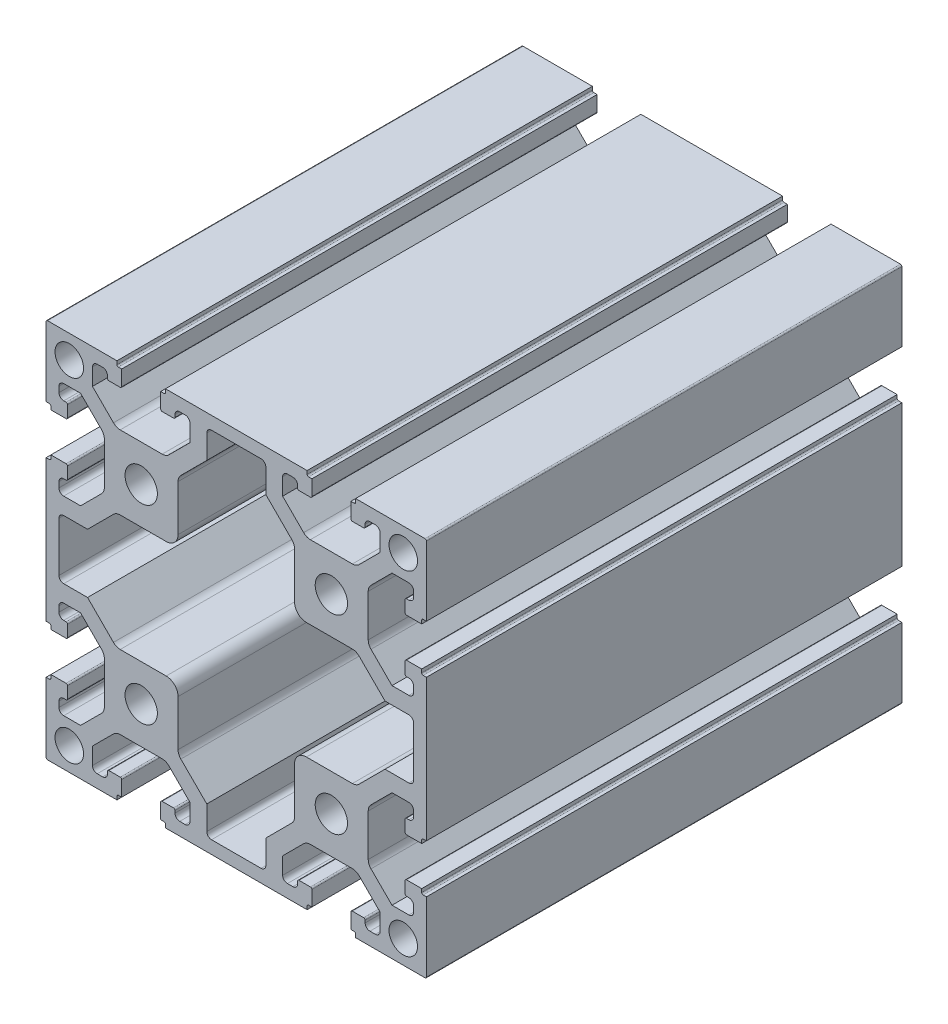
SolidWorks part; units mm, degrees
ref_plane "前视基准面" through (0, 0, 0) normal (0, 0, 1) x (1, 0, 0)
ref_plane "上视基准面" through (0, 0, 0) normal (0, 1, 0) x (1, 0, 0)
ref_plane "右视基准面" through (0, 0, 0) normal (1, 0, 0) x (0, 0, -1)
sketch "草图1" plane through (0, 0, 0) normal (0, 0, 1) x (1, 0, 0)
  line L0 (-25.5828, 38.6374) -> (-40.1828, 38.6374)
  line L1 (-40.4828, 38.3374) -> (-40.4828, 23.7374)
  line L2 (-33.236, 28.8874) -> (-36.7828, 28.8874)
  line L3 (-37.7828, 27.8874) -> (-37.7828, 26.7374)
  line L4 (-36.7828, 25.7374) -> (-36.2828, 25.7374)
  line L5 (-35.9828, 25.4374) -> (-35.9828, 23.0374)
  line L6 (-36.2828, 22.7374) -> (-39.4828, 22.7374)
  line L8 (-40.4828, 23.7374) -> (-39.7828, 23.7374)
  line L9 (-39.4828, 23.4374) -> (-39.4828, 22.7374)
  line L10 (-33.236, 28.8874) -> (-28.8186, 24.47)
  line L11 (-28.2328, 23.0558) -> (-28.2328, 14.219)
  line L12 (-28.8186, 12.8047) -> (-33.236, 8.3874)
  line L14 (-31.7697, 4.8474) -> (-26.3154, 10.3016)
  line L15 (-24.9012, 10.8874) -> (-15.2328, 10.8874)
  line L16 (-12.7328, 13.3874) -> (-12.7328, 23.0558)
  line L17 (-12.147, 24.47) -> (-6.6928, 29.9242)
  line L18 (-10.2328, 31.3905) -> (-14.6502, 26.9732)
  line L19 (-16.0644, 26.3874) -> (-24.9012, 26.3874)
  line L20 (-26.3154, 26.9732) -> (-30.7328, 31.3905)
  line L21 (-25.5828, 38.6374) -> (-25.5828, 37.9374)
  line L22 (-25.2828, 37.6374) -> (-24.5828, 37.6374)
  line L23 (-30.7328, 31.3905) -> (-30.7328, 34.9374)
  line L24 (-29.7328, 35.9374) -> (-28.5828, 35.9374)
  line L25 (-27.5828, 34.9374) -> (-27.5828, 34.4374)
  line L26 (-27.2828, 34.1374) -> (-24.8828, 34.1374)
  line L27 (-24.5828, 34.4374) -> (-24.5828, 37.6374)
  line L28 (-15.3828, 38.6374) -> (-4.9828, 38.6374)
  line L30 (-10.2328, 31.3905) -> (-10.2328, 34.9374)
  line L31 (-11.2328, 35.9374) -> (-12.3828, 35.9374)
  line L32 (-13.3828, 34.9374) -> (-13.3828, 34.4374)
  line L33 (-13.6828, 34.1374) -> (-16.0828, 34.1374)
  line L34 (-16.3828, 34.4374) -> (-16.3828, 37.6374)
  line L35 (-15.3828, 38.6374) -> (-15.3828, 37.9374)
  line L36 (-15.6828, 37.6374) -> (-16.3828, 37.6374)
  line L37 (-33.236, 8.3874) -> (-36.7828, 8.3874)
  line L38 (-37.7828, 9.3874) -> (-37.7828, 10.5374)
  line L39 (-36.7828, 11.5374) -> (-36.2828, 11.5374)
  line L40 (-35.9828, 11.8374) -> (-35.9828, 14.2374)
  line L41 (-36.2828, 14.5374) -> (-39.4828, 14.5374)
  line L42 (-40.4828, 13.5374) -> (-39.7828, 13.5374)
  line L43 (-39.4828, 13.8374) -> (-39.4828, 14.5374)
  line L44 (14.4172, 38.6374) -> (4.0172, 38.6374)
  line L47 (32.2703, 8.3874) -> (27.853, 12.8047)
  line L48 (27.2672, 14.219) -> (27.2672, 23.0558)
  line L49 (27.853, 24.47) -> (32.2703, 28.8874)
  line L50 (29.7672, 31.3905) -> (25.3498, 26.9732)
  line L51 (23.9356, 26.3874) -> (15.0988, 26.3874)
  line L52 (13.6846, 26.9732) -> (9.2672, 31.3905)
  line L53 (14.4172, 38.6374) -> (14.4172, 37.9374)
  line L54 (14.7172, 37.6374) -> (15.4172, 37.6374)
  line L55 (9.2672, 31.3905) -> (9.2672, 34.9374)
  line L56 (10.2672, 35.9374) -> (11.4172, 35.9374)
  line L57 (12.4172, 34.9374) -> (12.4172, 34.4374)
  line L58 (12.7172, 34.1374) -> (15.1172, 34.1374)
  line L59 (15.4172, 34.4374) -> (15.4172, 37.6374)
  line L60 (24.6172, 38.6374) -> (39.2172, 38.6374)
  line L61 (39.5172, 38.3374) -> (39.5172, 23.7374)
  line L62 (32.2703, 28.8874) -> (35.8172, 28.8874)
  line L63 (36.8172, 27.8874) -> (36.8172, 26.7374)
  line L64 (35.8172, 25.7374) -> (35.3172, 25.7374)
  line L65 (35.0172, 25.4374) -> (35.0172, 23.0374)
  line L66 (35.3172, 22.7374) -> (38.5172, 22.7374)
  line L68 (39.5172, 23.7374) -> (38.8172, 23.7374)
  line L69 (38.5172, 23.4374) -> (38.5172, 22.7374)
  line L70 (29.7672, 31.3905) -> (29.7672, 34.9374)
  line L71 (28.7672, 35.9374) -> (27.6172, 35.9374)
  line L72 (26.6172, 34.9374) -> (26.6172, 34.4374)
  line L73 (26.3172, 34.1374) -> (23.9172, 34.1374)
  line L74 (23.6172, 34.4374) -> (23.6172, 37.6374)
  line L75 (24.6172, 38.6374) -> (24.6172, 37.9374)
  line L76 (24.3172, 37.6374) -> (23.6172, 37.6374)
  line L77 (32.2703, 8.3874) -> (35.8172, 8.3874)
  line L78 (36.8172, 9.3874) -> (36.8172, 10.5374)
  line L79 (35.8172, 11.5374) -> (35.3172, 11.5374)
  line L80 (35.0172, 11.8374) -> (35.0172, 14.2374)
  line L81 (35.3172, 14.5374) -> (38.5172, 14.5374)
  line L82 (39.5172, 13.5374) -> (38.8172, 13.5374)
  line L83 (38.5172, 13.8374) -> (38.5172, 14.5374)
  line L84 (-4.9828, 38.6374) -> (4.0172, 38.6374)
  line L86 (-6.6928, 29.9242) -> (-6.6928, 34.9374)
  line L87 (-5.6928, 35.9374) -> (4.7272, 35.9374)
  line L88 (5.7272, 29.9242) -> (5.7272, 34.9374)
  line L89 (-25.5828, -41.3626) -> (-40.1828, -41.3626)
  line L90 (-40.4828, -41.0626) -> (-40.4828, -26.4626)
  line L91 (-33.236, -31.6126) -> (-36.7828, -31.6126)
  line L92 (-37.7828, -30.6126) -> (-37.7828, -29.4626)
  line L93 (-36.7828, -28.4626) -> (-36.2828, -28.4626)
  line L94 (-35.9828, -28.1626) -> (-35.9828, -25.7626)
  line L95 (-36.2828, -25.4626) -> (-39.4828, -25.4626)
  line L97 (-40.4828, -26.4626) -> (-39.7828, -26.4626)
  line L98 (-39.4828, -26.1626) -> (-39.4828, -25.4626)
  line L99 (-33.236, -31.6126) -> (-28.8186, -27.1953)
  line L100 (-28.2328, -25.781) -> (-28.2328, -16.9442)
  line L101 (-28.8186, -15.53) -> (-33.236, -11.1126)
  line L103 (-31.7697, -7.5726) -> (-26.3154, -13.0268)
  line L104 (-24.9012, -13.6126) -> (-15.2328, -13.6126)
  line L105 (-12.7328, -16.1126) -> (-12.7328, -25.781)
  line L106 (-12.147, -27.1953) -> (-6.6928, -32.6495)
  line L107 (-10.2328, -34.1158) -> (-14.6502, -29.6984)
  line L108 (-16.0644, -29.1126) -> (-24.9012, -29.1126)
  line L109 (-26.3154, -29.6984) -> (-30.7328, -34.1158)
  line L110 (-25.5828, -41.3626) -> (-25.5828, -40.6626)
  line L111 (-25.2828, -40.3626) -> (-24.5828, -40.3626)
  line L112 (-30.7328, -34.1158) -> (-30.7328, -37.6626)
  line L113 (-29.7328, -38.6626) -> (-28.5828, -38.6626)
  line L114 (-27.5828, -37.6626) -> (-27.5828, -37.1626)
  line L115 (-27.2828, -36.8626) -> (-24.8828, -36.8626)
  line L116 (-24.5828, -37.1626) -> (-24.5828, -40.3626)
  line L117 (-15.3828, -41.3626) -> (-4.9828, -41.3626)
  line L120 (-11.2328, -38.6626) -> (-12.3828, -38.6626)
  line L121 (-13.3828, -37.6626) -> (-13.3828, -37.1626)
  line L122 (-13.6828, -36.8626) -> (-16.0828, -36.8626)
  line L123 (-16.3828, -37.1626) -> (-16.3828, -40.3626)
  line L124 (-15.3828, -41.3626) -> (-15.3828, -40.6626)
  line L125 (-15.6828, -40.3626) -> (-16.3828, -40.3626)
  line L126 (-33.236, -11.1126) -> (-36.7828, -11.1126)
  line L127 (-37.7828, -12.1126) -> (-37.7828, -13.2626)
  line L128 (-36.7828, -14.2626) -> (-36.2828, -14.2626)
  line L129 (-35.9828, -14.5626) -> (-35.9828, -16.9626)
  line L130 (-36.2828, -17.2626) -> (-39.4828, -17.2626)
  line L131 (-40.4828, -16.2626) -> (-39.7828, -16.2626)
  line L132 (-39.4828, -16.5626) -> (-39.4828, -17.2626)
  line L133 (14.4172, -41.3626) -> (4.0172, -41.3626)
  line L135 (5.7272, -32.6495) -> (11.1814, -27.1953)
  line L136 (11.7672, -25.781) -> (11.7672, -16.1126)
  line L137 (14.2672, -13.6126) -> (23.9356, -13.6126)
  line L138 (25.3498, -13.0268) -> (30.804, -7.5726)
  line L140 (32.2703, -11.1126) -> (27.853, -15.53)
  line L141 (27.2672, -16.9442) -> (27.2672, -25.781)
  line L142 (27.853, -27.1953) -> (32.2703, -31.6126)
  line L143 (29.7672, -34.1158) -> (25.3498, -29.6984)
  line L144 (23.9356, -29.1126) -> (15.0988, -29.1126)
  line L145 (13.6846, -29.6984) -> (9.2672, -34.1158)
  line L146 (14.4172, -41.3626) -> (14.4172, -40.6626)
  line L147 (14.7172, -40.3626) -> (15.4172, -40.3626)
  line L148 (9.2672, -34.1158) -> (9.2672, -37.6626)
  line L149 (10.2672, -38.6626) -> (11.4172, -38.6626)
  line L150 (12.4172, -37.6626) -> (12.4172, -37.1626)
  line L151 (12.7172, -36.8626) -> (15.1172, -36.8626)
  line L152 (15.4172, -37.1626) -> (15.4172, -40.3626)
  line L153 (24.6172, -41.3626) -> (39.2172, -41.3626)
  line L154 (39.5172, -41.0626) -> (39.5172, -26.4626)
  line L155 (32.2703, -31.6126) -> (35.8172, -31.6126)
  line L156 (36.8172, -30.6126) -> (36.8172, -29.4626)
  line L157 (35.8172, -28.4626) -> (35.3172, -28.4626)
  line L158 (35.0172, -28.1626) -> (35.0172, -25.7626)
  line L159 (35.3172, -25.4626) -> (38.5172, -25.4626)
  line L161 (39.5172, -26.4626) -> (38.8172, -26.4626)
  line L162 (38.5172, -26.1626) -> (38.5172, -25.4626)
  line L163 (29.7672, -34.1158) -> (29.7672, -37.6626)
  line L164 (28.7672, -38.6626) -> (27.6172, -38.6626)
  line L165 (26.6172, -37.6626) -> (26.6172, -37.1626)
  line L166 (26.3172, -36.8626) -> (23.9172, -36.8626)
  line L167 (23.6172, -37.1626) -> (23.6172, -40.3626)
  line L168 (24.6172, -41.3626) -> (24.6172, -40.6626)
  line L169 (24.3172, -40.3626) -> (23.6172, -40.3626)
  line L170 (32.2703, -11.1126) -> (35.8172, -11.1126)
  line L171 (36.8172, -12.1126) -> (36.8172, -13.2626)
  line L172 (35.8172, -14.2626) -> (35.3172, -14.2626)
  line L173 (35.0172, -14.5626) -> (35.0172, -16.9626)
  line L174 (35.3172, -17.2626) -> (38.5172, -17.2626)
  line L175 (39.5172, -16.2626) -> (38.8172, -16.2626)
  line L176 (38.5172, -16.5626) -> (38.5172, -17.2626)
  line L177 (-4.9828, -41.3626) -> (4.0172, -41.3626)
  line L178 (-10.2328, -34.1158) -> (-10.2328, -37.6626)
  line L179 (-6.6928, -32.6495) -> (-6.6928, -37.6626)
  line L180 (-5.6928, -38.6626) -> (4.7272, -38.6626)
  line L181 (5.7272, -32.6495) -> (5.7272, -37.6626)
  line L182 (-31.7697, 4.8474) -> (-36.7828, 4.8474)
  line L183 (-37.7828, 3.8474) -> (-37.7828, -6.5726)
  line L184 (-31.7697, -7.5726) -> (-36.7828, -7.5726)
  line L185 (-40.4828, 13.5374) -> (-40.4828, 3.1374)
  line L186 (-40.4828, -16.2626) -> (-40.4828, -5.8626)
  line L187 (-40.4828, 3.1374) -> (-40.4828, -5.8626)
  line L188 (5.7272, 29.9242) -> (11.1814, 24.47)
  line L189 (11.7672, 23.0558) -> (11.7672, 13.3874)
  line L190 (14.2672, 10.8874) -> (23.9356, 10.8874)
  line L191 (25.3498, 10.3016) -> (30.804, 4.8474)
  line L192 (30.804, 4.8474) -> (35.8172, 4.8474)
  line L193 (36.8172, 3.8474) -> (36.8172, -6.5726)
  line L194 (30.804, -7.5726) -> (35.8172, -7.5726)
  line L195 (39.5172, 13.5374) -> (39.5172, 3.1374)
  line L196 (39.5172, -16.2626) -> (39.5172, -5.8626)
  line L197 (39.5172, 3.1374) -> (39.5172, -5.8626)
  arc A0 (-40.1828, 38.6374) -> (-40.4828, 38.3374) centre (-40.1828, 38.3374) ccw
  arc A1 (-36.7828, 28.8874) -> (-37.7828, 27.8874) centre (-36.7828, 27.8874) ccw
  arc A2 (-37.7828, 26.7374) -> (-36.7828, 25.7374) centre (-36.7828, 26.7374) ccw
  arc A3 (-35.9828, 25.4374) -> (-36.2828, 25.7374) centre (-36.2828, 25.4374) ccw
  arc A4 (-36.2828, 22.7374) -> (-35.9828, 23.0374) centre (-36.2828, 23.0374) ccw
  arc A5 (-39.4828, 23.4374) -> (-39.7828, 23.7374) centre (-39.7828, 23.4374) ccw
  arc A6 (-28.2328, 23.0558) -> (-28.8186, 24.47) centre (-30.2328, 23.0558) ccw
  arc A7 (-28.8186, 12.8047) -> (-28.2328, 14.219) centre (-30.2328, 14.219) ccw
  arc A8 (-24.9012, 10.8874) -> (-26.3154, 10.3016) centre (-24.9012, 8.8874) ccw
  arc A9 (-15.2328, 10.8874) -> (-12.7328, 13.3874) centre (-15.2328, 13.3874) ccw
  arc A10 (-12.147, 24.47) -> (-12.7328, 23.0558) centre (-10.7328, 23.0558) ccw
  arc A11 (-16.0644, 26.3874) -> (-14.6502, 26.9732) centre (-16.0644, 28.3874) ccw
  arc A12 (-26.3154, 26.9732) -> (-24.9012, 26.3874) centre (-24.9012, 28.3874) ccw
  circle A13 centre (-20.4828, 18.6374) radius 3.4
  circle A14 centre (-35.6078, 33.7624) radius 3
  arc A15 (-25.5828, 37.9374) -> (-25.2828, 37.6374) centre (-25.2828, 37.9374) ccw
  arc A16 (-29.7328, 35.9374) -> (-30.7328, 34.9374) centre (-29.7328, 34.9374) ccw
  arc A17 (-27.5828, 34.9374) -> (-28.5828, 35.9374) centre (-28.5828, 34.9374) ccw
  arc A18 (-27.5828, 34.4374) -> (-27.2828, 34.1374) centre (-27.2828, 34.4374) ccw
  arc A19 (-24.8828, 34.1374) -> (-24.5828, 34.4374) centre (-24.8828, 34.4374) ccw
  arc A20 (-10.2328, 34.9374) -> (-11.2328, 35.9374) centre (-11.2328, 34.9374) ccw
  arc A21 (-12.3828, 35.9374) -> (-13.3828, 34.9374) centre (-12.3828, 34.9374) ccw
  arc A22 (-13.6828, 34.1374) -> (-13.3828, 34.4374) centre (-13.6828, 34.4374) ccw
  arc A23 (-16.3828, 34.4374) -> (-16.0828, 34.1374) centre (-16.0828, 34.4374) ccw
  arc A24 (-15.6828, 37.6374) -> (-15.3828, 37.9374) centre (-15.6828, 37.9374) ccw
  arc A25 (-37.7828, 9.3874) -> (-36.7828, 8.3874) centre (-36.7828, 9.3874) ccw
  arc A26 (-36.7828, 11.5374) -> (-37.7828, 10.5374) centre (-36.7828, 10.5374) ccw
  arc A27 (-36.2828, 11.5374) -> (-35.9828, 11.8374) centre (-36.2828, 11.8374) ccw
  arc A28 (-35.9828, 14.2374) -> (-36.2828, 14.5374) centre (-36.2828, 14.2374) ccw
  arc A29 (-39.7828, 13.5374) -> (-39.4828, 13.8374) centre (-39.7828, 13.8374) ccw
  arc A30 (27.2672, 14.219) -> (27.853, 12.8047) centre (29.2672, 14.219) ccw
  arc A31 (27.853, 24.47) -> (27.2672, 23.0558) centre (29.2672, 23.0558) ccw
  arc A32 (23.9356, 26.3874) -> (25.3498, 26.9732) centre (23.9356, 28.3874) ccw
  arc A33 (13.6846, 26.9732) -> (15.0988, 26.3874) centre (15.0988, 28.3874) ccw
  circle A34 centre (19.5172, 18.6374) radius 3.4
  arc A35 (14.4172, 37.9374) -> (14.7172, 37.6374) centre (14.7172, 37.9374) ccw
  arc A36 (10.2672, 35.9374) -> (9.2672, 34.9374) centre (10.2672, 34.9374) ccw
  arc A37 (12.4172, 34.9374) -> (11.4172, 35.9374) centre (11.4172, 34.9374) ccw
  arc A38 (12.4172, 34.4374) -> (12.7172, 34.1374) centre (12.7172, 34.4374) ccw
  arc A39 (15.1172, 34.1374) -> (15.4172, 34.4374) centre (15.1172, 34.4374) ccw
  arc A40 (39.5172, 38.3374) -> (39.2172, 38.6374) centre (39.2172, 38.3374) ccw
  arc A41 (36.8172, 27.8874) -> (35.8172, 28.8874) centre (35.8172, 27.8874) ccw
  arc A42 (35.8172, 25.7374) -> (36.8172, 26.7374) centre (35.8172, 26.7374) ccw
  arc A43 (35.3172, 25.7374) -> (35.0172, 25.4374) centre (35.3172, 25.4374) ccw
  arc A44 (35.0172, 23.0374) -> (35.3172, 22.7374) centre (35.3172, 23.0374) ccw
  arc A45 (38.8172, 23.7374) -> (38.5172, 23.4374) centre (38.8172, 23.4374) ccw
  circle A46 centre (34.6422, 33.7624) radius 3
  arc A47 (29.7672, 34.9374) -> (28.7672, 35.9374) centre (28.7672, 34.9374) ccw
  arc A48 (27.6172, 35.9374) -> (26.6172, 34.9374) centre (27.6172, 34.9374) ccw
  arc A49 (26.3172, 34.1374) -> (26.6172, 34.4374) centre (26.3172, 34.4374) ccw
  arc A50 (23.6172, 34.4374) -> (23.9172, 34.1374) centre (23.9172, 34.4374) ccw
  arc A51 (24.3172, 37.6374) -> (24.6172, 37.9374) centre (24.3172, 37.9374) ccw
  arc A52 (35.8172, 8.3874) -> (36.8172, 9.3874) centre (35.8172, 9.3874) ccw
  arc A53 (36.8172, 10.5374) -> (35.8172, 11.5374) centre (35.8172, 10.5374) ccw
  arc A54 (35.0172, 11.8374) -> (35.3172, 11.5374) centre (35.3172, 11.8374) ccw
  arc A55 (35.3172, 14.5374) -> (35.0172, 14.2374) centre (35.3172, 14.2374) ccw
  arc A56 (38.5172, 13.8374) -> (38.8172, 13.5374) centre (38.8172, 13.8374) ccw
  arc A57 (-5.6928, 35.9374) -> (-6.6928, 34.9374) centre (-5.6928, 34.9374) ccw
  arc A58 (5.7272, 34.9374) -> (4.7272, 35.9374) centre (4.7272, 34.9374) ccw
  arc A59 (-40.4828, -41.0626) -> (-40.1828, -41.3626) centre (-40.1828, -41.0626) ccw
  arc A60 (-37.7828, -30.6126) -> (-36.7828, -31.6126) centre (-36.7828, -30.6126) ccw
  arc A61 (-36.7828, -28.4626) -> (-37.7828, -29.4626) centre (-36.7828, -29.4626) ccw
  arc A62 (-36.2828, -28.4626) -> (-35.9828, -28.1626) centre (-36.2828, -28.1626) ccw
  arc A63 (-35.9828, -25.7626) -> (-36.2828, -25.4626) centre (-36.2828, -25.7626) ccw
  arc A64 (-39.7828, -26.4626) -> (-39.4828, -26.1626) centre (-39.7828, -26.1626) ccw
  arc A65 (-28.8186, -27.1953) -> (-28.2328, -25.781) centre (-30.2328, -25.781) ccw
  arc A66 (-28.2328, -16.9442) -> (-28.8186, -15.53) centre (-30.2328, -16.9442) ccw
  arc A67 (-26.3154, -13.0268) -> (-24.9012, -13.6126) centre (-24.9012, -11.6126) ccw
  arc A68 (-12.7328, -16.1126) -> (-15.2328, -13.6126) centre (-15.2328, -16.1126) ccw
  arc A69 (-12.7328, -25.781) -> (-12.147, -27.1953) centre (-10.7328, -25.781) ccw
  arc A70 (-14.6502, -29.6984) -> (-16.0644, -29.1126) centre (-16.0644, -31.1126) ccw
  arc A71 (-24.9012, -29.1126) -> (-26.3154, -29.6984) centre (-24.9012, -31.1126) ccw
  circle A72 centre (-20.4828, -21.3626) radius 3.4
  circle A73 centre (-35.6078, -36.4876) radius 3
  arc A74 (-25.2828, -40.3626) -> (-25.5828, -40.6626) centre (-25.2828, -40.6626) ccw
  arc A75 (-30.7328, -37.6626) -> (-29.7328, -38.6626) centre (-29.7328, -37.6626) ccw
  arc A76 (-28.5828, -38.6626) -> (-27.5828, -37.6626) centre (-28.5828, -37.6626) ccw
  arc A77 (-27.2828, -36.8626) -> (-27.5828, -37.1626) centre (-27.2828, -37.1626) ccw
  arc A78 (-24.5828, -37.1626) -> (-24.8828, -36.8626) centre (-24.8828, -37.1626) ccw
  arc A79 (-11.2328, -38.6626) -> (-10.2328, -37.6626) centre (-11.2328, -37.6626) ccw
  arc A80 (-13.3828, -37.6626) -> (-12.3828, -38.6626) centre (-12.3828, -37.6626) ccw
  arc A81 (-13.3828, -37.1626) -> (-13.6828, -36.8626) centre (-13.6828, -37.1626) ccw
  arc A82 (-16.0828, -36.8626) -> (-16.3828, -37.1626) centre (-16.0828, -37.1626) ccw
  arc A83 (-15.3828, -40.6626) -> (-15.6828, -40.3626) centre (-15.6828, -40.6626) ccw
  arc A84 (-36.7828, -11.1126) -> (-37.7828, -12.1126) centre (-36.7828, -12.1126) ccw
  arc A85 (-37.7828, -13.2626) -> (-36.7828, -14.2626) centre (-36.7828, -13.2626) ccw
  arc A86 (-35.9828, -14.5626) -> (-36.2828, -14.2626) centre (-36.2828, -14.5626) ccw
  arc A87 (-36.2828, -17.2626) -> (-35.9828, -16.9626) centre (-36.2828, -16.9626) ccw
  arc A88 (-39.4828, -16.5626) -> (-39.7828, -16.2626) centre (-39.7828, -16.5626) ccw
  arc A89 (11.1814, -27.1953) -> (11.7672, -25.781) centre (9.7672, -25.781) ccw
  arc A90 (14.2672, -13.6126) -> (11.7672, -16.1126) centre (14.2672, -16.1126) ccw
  arc A91 (23.9356, -13.6126) -> (25.3498, -13.0268) centre (23.9356, -11.6126) ccw
  arc A92 (27.853, -15.53) -> (27.2672, -16.9442) centre (29.2672, -16.9442) ccw
  arc A93 (27.2672, -25.781) -> (27.853, -27.1953) centre (29.2672, -25.781) ccw
  arc A94 (25.3498, -29.6984) -> (23.9356, -29.1126) centre (23.9356, -31.1126) ccw
  arc A95 (15.0988, -29.1126) -> (13.6846, -29.6984) centre (15.0988, -31.1126) ccw
  circle A96 centre (19.5172, -21.3626) radius 3.4
  arc A97 (14.7172, -40.3626) -> (14.4172, -40.6626) centre (14.7172, -40.6626) ccw
  arc A98 (9.2672, -37.6626) -> (10.2672, -38.6626) centre (10.2672, -37.6626) ccw
  arc A99 (11.4172, -38.6626) -> (12.4172, -37.6626) centre (11.4172, -37.6626) ccw
  arc A100 (12.7172, -36.8626) -> (12.4172, -37.1626) centre (12.7172, -37.1626) ccw
  arc A101 (15.4172, -37.1626) -> (15.1172, -36.8626) centre (15.1172, -37.1626) ccw
  arc A102 (39.2172, -41.3626) -> (39.5172, -41.0626) centre (39.2172, -41.0626) ccw
  arc A103 (35.8172, -31.6126) -> (36.8172, -30.6126) centre (35.8172, -30.6126) ccw
  arc A104 (36.8172, -29.4626) -> (35.8172, -28.4626) centre (35.8172, -29.4626) ccw
  arc A105 (35.0172, -28.1626) -> (35.3172, -28.4626) centre (35.3172, -28.1626) ccw
  arc A106 (35.3172, -25.4626) -> (35.0172, -25.7626) centre (35.3172, -25.7626) ccw
  arc A107 (38.5172, -26.1626) -> (38.8172, -26.4626) centre (38.8172, -26.1626) ccw
  circle A108 centre (34.6422, -36.4876) radius 3
  arc A109 (28.7672, -38.6626) -> (29.7672, -37.6626) centre (28.7672, -37.6626) ccw
  arc A110 (26.6172, -37.6626) -> (27.6172, -38.6626) centre (27.6172, -37.6626) ccw
  arc A111 (26.6172, -37.1626) -> (26.3172, -36.8626) centre (26.3172, -37.1626) ccw
  arc A112 (23.9172, -36.8626) -> (23.6172, -37.1626) centre (23.9172, -37.1626) ccw
  arc A113 (24.6172, -40.6626) -> (24.3172, -40.3626) centre (24.3172, -40.6626) ccw
  arc A114 (36.8172, -12.1126) -> (35.8172, -11.1126) centre (35.8172, -12.1126) ccw
  arc A115 (35.8172, -14.2626) -> (36.8172, -13.2626) centre (35.8172, -13.2626) ccw
  arc A116 (35.3172, -14.2626) -> (35.0172, -14.5626) centre (35.3172, -14.5626) ccw
  arc A117 (35.0172, -16.9626) -> (35.3172, -17.2626) centre (35.3172, -16.9626) ccw
  arc A118 (38.8172, -16.2626) -> (38.5172, -16.5626) centre (38.8172, -16.5626) ccw
  arc A119 (-6.6928, -37.6626) -> (-5.6928, -38.6626) centre (-5.6928, -37.6626) ccw
  arc A120 (4.7272, -38.6626) -> (5.7272, -37.6626) centre (4.7272, -37.6626) ccw
  arc A121 (-36.7828, 4.8474) -> (-37.7828, 3.8474) centre (-36.7828, 3.8474) ccw
  arc A122 (-37.7828, -6.5726) -> (-36.7828, -7.5726) centre (-36.7828, -6.5726) ccw
  arc A123 (11.7672, 23.0558) -> (11.1814, 24.47) centre (9.7672, 23.0558) ccw
  arc A124 (11.7672, 13.3874) -> (14.2672, 10.8874) centre (14.2672, 13.3874) ccw
  arc A125 (25.3498, 10.3016) -> (23.9356, 10.8874) centre (23.9356, 8.8874) ccw
  arc A126 (36.8172, 3.8474) -> (35.8172, 4.8474) centre (35.8172, 3.8474) ccw
  arc A127 (35.8172, -7.5726) -> (36.8172, -6.5726) centre (35.8172, -6.5726) ccw
extrude "凸台-拉伸1" add sketch "草图1" along normal blind 100
